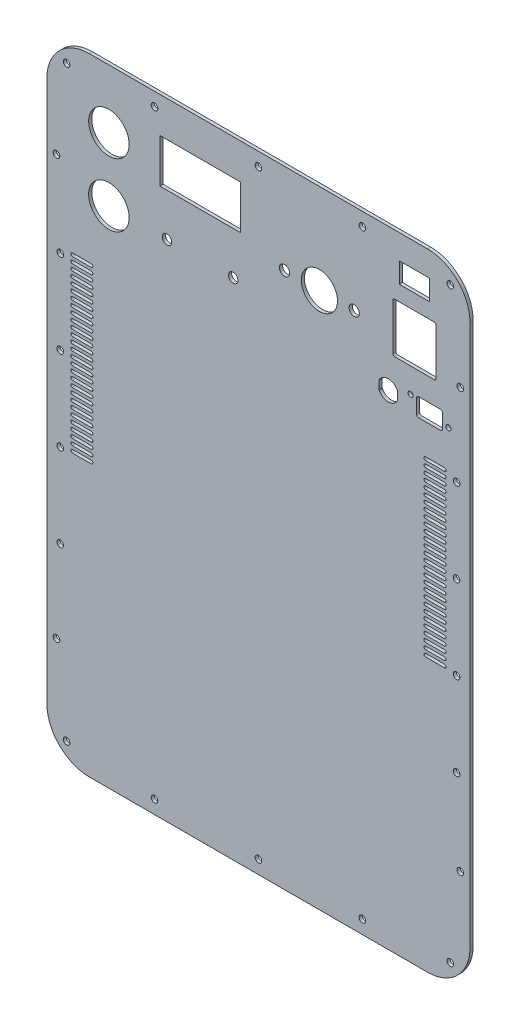
SolidWorks part; units mm, degrees
ref_plane "Alzado" through (0, 0, 0) normal (0, 0, 1) x (1, 0, 0)
ref_plane "Planta" through (0, 0, 0) normal (0, 1, 0) x (1, 0, 0)
ref_plane "Vista lateral" through (0, 0, 0) normal (1, 0, 0) x (0, 0, -1)
sketch "Croquis1" plane through (0, 0, 0) normal (0, 0, 1) x (1, 0, 0)
  line L1 (-107.295, -198.81) -> (107.295, -198.81)
  line L2 (-134.295, -171.81) -> (-134.295, 171.81)
  line L3 (-107.295, 198.81) -> (107.295, 198.81)
  line L4 (134.295, -171.81) -> (134.295, 171.81)
  line L5 (-134.295, -198.81) -> (134.295, 198.81) construction
  line L6 (-134.295, 198.81) -> (134.295, -198.81) construction
  arc A0 (-107.295, -198.81) -> (-134.295, -171.81) centre (-107.295, -171.81) cw
  arc A1 (107.295, -198.81) -> (134.295, -171.81) centre (107.295, -171.81) ccw
  arc A2 (107.295, 198.81) -> (134.295, 171.81) centre (107.295, 171.81) cw
  arc A3 (-134.295, 171.81) -> (-107.295, 198.81) centre (-107.295, 171.81) cw
  point P0 (0, 0)
  dimension "D3" = 27
  dimension "D1" = 268.59
  dimension "D2" = 397.62
extrude "Saliente-Extruir1" add sketch "Croquis1" along normal blind 2
sketch "Croquis2" plane through (0, 0, 2) normal (0, 0, 1) x (1, 0, 0)
  line L0 (107.295, 198.81) -> (-107.295, 198.81) construction
  line L1 (-134.295, 171.81) -> (-134.295, -171.81) construction
  line L2 (134.295, -171.81) -> (134.295, 171.81) construction
  line L4 (-62.615, 148.39) -> (-11.315, 148.39)
  line L5 (-62.615, 148.39) -> (-62.615, 176.19)
  line L6 (-62.615, 176.19) -> (-11.315, 176.19)
  line L7 (-11.315, 148.39) -> (-11.315, 176.19)
  line L8 (-62.615, 148.39) -> (-11.315, 176.19) construction
  line L9 (-62.615, 176.19) -> (-11.315, 148.39) construction
  line L10 (89.385, 170.39) -> (108.685, 170.39)
  line L11 (89.385, 170.39) -> (89.385, 183.29)
  line L12 (89.385, 183.29) -> (108.685, 183.29)
  line L13 (108.685, 170.39) -> (108.685, 183.29)
  line L14 (89.385, 170.39) -> (108.685, 183.29) construction
  line L15 (89.385, 183.29) -> (108.685, 170.39) construction
  line L16 (86.385, 129.09) -> (111.685, 129.09)
  line L17 (85.385, 130.09) -> (85.385, 159.69)
  line L18 (86.385, 160.69) -> (111.685, 160.69)
  line L19 (112.685, 130.09) -> (112.685, 159.69)
  line L20 (85.385, 129.09) -> (112.685, 160.69) construction
  line L21 (85.385, 160.69) -> (112.685, 129.09) construction
  line L22 (101.67, 103.165) -> (115.46, 103.165)
  line L23 (100.29, 104.545) -> (100.29, 113.335)
  line L24 (101.67, 114.715) -> (115.46, 114.715)
  line L25 (116.84, 104.545) -> (116.84, 113.335)
  line L26 (100.29, 103.165) -> (116.84, 114.715) construction
  line L27 (100.29, 114.715) -> (116.84, 103.165) construction
  line L29 (76.59, 105.9387) -> (76.59, 111.2413)
  line L31 (88.24, 105.9387) -> (88.24, 111.2413)
  line L32 (76.6043, 105.9076) -> (88.2257, 111.2724) construction
  line L33 (76.59, 111.279) -> (88.2257, 105.9076) construction
  circle A0 centre (-94.915, 161.54) radius 12.85
  circle A1 centre (-94.915, 121.27) radius 12.85
  circle A2 centre (-58.015, 121.27) radius 3
  circle A3 centre (-16.015, 121.27) radius 3
  circle A4 centre (38.695, 141.62) radius 11.5
  circle A5 centre (16.595, 141.62) radius 3.25
  circle A6 centre (60.795, 141.62) radius 3.25
  arc A7 (111.685, 129.09) -> (112.685, 130.09) centre (111.685, 130.09) ccw
  arc A8 (86.385, 129.09) -> (85.385, 130.09) centre (86.385, 130.09) cw
  arc A9 (85.385, 159.69) -> (86.385, 160.69) centre (86.385, 159.69) cw
  arc A10 (111.685, 160.69) -> (112.685, 159.69) centre (111.685, 159.69) cw
  circle A11 centre (120.565, 107.09) radius 1.625
  circle A12 centre (96.565, 113.44) radius 1.625
  arc A13 (100.29, 113.335) -> (101.67, 114.715) centre (101.67, 113.335) cw
  arc A14 (101.67, 103.165) -> (100.29, 104.545) centre (101.67, 104.545) cw
  arc A15 (115.46, 103.165) -> (116.84, 104.545) centre (115.46, 104.545) ccw
  arc A16 (115.46, 114.715) -> (116.84, 113.335) centre (115.46, 113.335) cw
  arc A17 (76.59, 105.9387) -> (88.24, 105.9387) centre (82.415, 108.59) ccw
  arc A18 (88.24, 111.2413) -> (76.59, 111.2413) centre (82.415, 108.59) ccw
  point P18 (99.035, 176.84)
  point P24 (-36.965, 162.29)
  point P30 (99.035, 144.89)
  point P47 (108.565, 108.94)
  dimension "D1" = 25.7
  dimension "D2" = 37.27
  dimension "D3" = 39.38
  dimension "D4" = 40.27
  dimension "D5" = 39.38
  dimension "D6" = 6
  dimension "D7" = 42
  dimension "D8" = 36.9
  dimension "D9" = 77.54
  dimension "D10" = 77.54
  dimension "D11" = 57.19
  dimension "D12" = 6.5
  dimension "D13" = 22.1
  dimension "D14" = 22.1
  dimension "D15" = 23
  dimension "D16" = 95.6
  dimension "D29" = 1
  dimension "D32" = 1.85
  dimension "D33" = 6.35
  dimension "D36" = 3.25
  dimension "D37" = 1.38
  dimension "D38" = 24
  dimension "D40" = 12.8
  dimension "D17" = 51.3
  dimension "D18" = 27.8
  dimension "D19" = 36.52
  dimension "D20" = 97.33
  dimension "D21" = 19.3
  dimension "D22" = 12.9
  dimension "D23" = 21.97
  dimension "D24" = 35.26
  dimension "D25" = 27.3
  dimension "D26" = 31.6
  dimension "D27" = 53.92
  dimension "D28" = 35.26
  dimension "D30" = 11.55
  dimension "D31" = 16.55
  dimension "D34" = 25.73
  dimension "D35" = 89.87
  dimension "D39" = 12
  dimension "D41" = 11.65
  dimension "D42" = 90.22
  dimension "D43" = 51.88
extrude "Cortar-Extruir1" cut sketch "Croquis2" against normal through all
sketch "Croquis3" plane through (0, 0, 2) normal (0, 0, 1) x (1, 0, 0)
  line L0 (0, 217.0296) -> (0, -209.3) construction
  line L1 (148.9664, 0) -> (-157.6291, 0) construction
  line L2 (107.295, 198.81) -> (-107.295, 198.81) construction
  line L3 (-134.295, 171.81) -> (-134.295, -171.81) construction
  circle A0 centre (0, 190.26) radius 2.095
  circle A1 centre (-65.96, 190.26) radius 2.095
  circle A2 centre (-121.78, 186.3) radius 2.095
  circle A3 centre (65.96, 190.26) radius 2.095
  circle A4 centre (121.78, 186.3) radius 2.095
  circle A5 centre (121.78, -186.3) radius 2.095
  circle A6 centre (65.96, -190.26) radius 2.095
  circle A7 centre (0, -190.26) radius 2.095
  circle A8 centre (-65.96, -190.26) radius 2.095
  circle A9 centre (-121.78, -186.3) radius 2.095
  circle A10 centre (-125.745, 26.61) radius 2.095
  circle A11 centre (-125.745, 79.83) radius 2.095
  circle A12 centre (-128.165, 133.05) radius 2.095
  circle A13 centre (-125.745, -26.61) radius 2.095
  circle A14 centre (-125.745, -79.83) radius 2.095
  circle A15 centre (-128.165, -133.05) radius 2.095
  circle A16 centre (128.165, -133.05) radius 2.095
  circle A17 centre (125.745, -79.83) radius 2.095
  circle A18 centre (125.745, -26.61) radius 2.095
  circle A19 centre (125.745, 26.61) radius 2.095
  circle A20 centre (125.745, 79.83) radius 2.095
  circle A21 centre (128.165, 133.05) radius 2.095
  dimension "D1" = 4.19
  dimension "D2" = 8.55
  dimension "D3" = 65.96
  dimension "D4" = 55.82
  dimension "D5" = 12.51
  dimension "D7" = 4.19
  dimension "D8" = 8.55
  dimension "D9" = 26.61
  dimension "D10" = 53.22
  dimension "D11" = 8.55
  dimension "D12" = 53.22
  dimension "D13" = 6.13
  dimension "D6" = 8.55
extrude "Cortar-Extruir2" cut sketch "Croquis3" against normal through all
sketch "Croquis4" plane through (0, 0, 2) normal (0, 0, 1) x (1, 0, 0)
  line L0 (0, 198.81) -> (0, -99.1567) construction
  line L1 (107.295, 198.81) -> (-107.295, 198.81) construction
  line L2 (-118.065, 82.89) -> (-106.065, 82.89) construction
  line L3 (-118.065, 83.89) -> (-106.065, 83.89)
  line L4 (-118.065, 81.89) -> (-106.065, 81.89)
  line L6 (-134.295, 171.81) -> (-134.295, -171.81) construction
  line L7 (-118.065, 78.89) -> (-106.065, 78.89) construction
  line L8 (-118.065, 79.89) -> (-106.065, 79.89)
  line L9 (-118.065, 77.89) -> (-106.065, 77.89)
  line L10 (-118.065, 74.89) -> (-106.065, 74.89) construction
  line L11 (-118.065, 75.89) -> (-106.065, 75.89)
  line L12 (-118.065, 73.89) -> (-106.065, 73.89)
  line L13 (-118.065, 70.89) -> (-106.065, 70.89) construction
  line L14 (-118.065, 71.89) -> (-106.065, 71.89)
  line L15 (-118.065, 69.89) -> (-106.065, 69.89)
  line L16 (-118.065, 66.89) -> (-106.065, 66.89) construction
  line L17 (-118.065, 67.89) -> (-106.065, 67.89)
  line L18 (-118.065, 65.89) -> (-106.065, 65.89)
  line L19 (-118.065, 62.89) -> (-106.065, 62.89) construction
  line L20 (-118.065, 63.89) -> (-106.065, 63.89)
  line L21 (-118.065, 61.89) -> (-106.065, 61.89)
  line L22 (-118.065, 58.89) -> (-106.065, 58.89) construction
  line L23 (-118.065, 59.89) -> (-106.065, 59.89)
  line L24 (-118.065, 57.89) -> (-106.065, 57.89)
  line L25 (-118.065, 54.89) -> (-106.065, 54.89) construction
  line L26 (-118.065, 55.89) -> (-106.065, 55.89)
  line L27 (-118.065, 53.89) -> (-106.065, 53.89)
  line L28 (-118.065, 50.89) -> (-106.065, 50.89) construction
  line L29 (-118.065, 51.89) -> (-106.065, 51.89)
  line L30 (-118.065, 49.89) -> (-106.065, 49.89)
  line L31 (-118.065, 46.89) -> (-106.065, 46.89) construction
  line L32 (-118.065, 47.89) -> (-106.065, 47.89)
  line L33 (-118.065, 45.89) -> (-106.065, 45.89)
  line L34 (-118.065, 42.89) -> (-106.065, 42.89) construction
  line L35 (-118.065, 43.89) -> (-106.065, 43.89)
  line L36 (-118.065, 41.89) -> (-106.065, 41.89)
  line L37 (-118.065, 38.89) -> (-106.065, 38.89) construction
  line L38 (-118.065, 39.89) -> (-106.065, 39.89)
  line L39 (-118.065, 37.89) -> (-106.065, 37.89)
  line L40 (-118.065, 34.89) -> (-106.065, 34.89) construction
  line L41 (-118.065, 35.89) -> (-106.065, 35.89)
  line L42 (-118.065, 33.89) -> (-106.065, 33.89)
  line L43 (-118.065, 30.89) -> (-106.065, 30.89) construction
  line L44 (-118.065, 31.89) -> (-106.065, 31.89)
  line L45 (-118.065, 29.89) -> (-106.065, 29.89)
  line L46 (-118.065, 26.89) -> (-106.065, 26.89) construction
  line L47 (-118.065, 27.89) -> (-106.065, 27.89)
  line L48 (-118.065, 25.89) -> (-106.065, 25.89)
  line L49 (-118.065, 22.89) -> (-106.065, 22.89) construction
  line L50 (-118.065, 23.89) -> (-106.065, 23.89)
  line L51 (-118.065, 21.89) -> (-106.065, 21.89)
  line L52 (-118.065, 18.89) -> (-106.065, 18.89) construction
  line L53 (-118.065, 19.89) -> (-106.065, 19.89)
  line L54 (-118.065, 17.89) -> (-106.065, 17.89)
  line L55 (-118.065, 14.89) -> (-106.065, 14.89) construction
  line L56 (-118.065, 15.89) -> (-106.065, 15.89)
  line L57 (-118.065, 13.89) -> (-106.065, 13.89)
  line L58 (-118.065, 10.89) -> (-106.065, 10.89) construction
  line L59 (-118.065, 11.89) -> (-106.065, 11.89)
  line L60 (-118.065, 9.89) -> (-106.065, 9.89)
  line L61 (-118.065, 6.89) -> (-106.065, 6.89) construction
  line L62 (-118.065, 7.89) -> (-106.065, 7.89)
  line L63 (-118.065, 5.89) -> (-106.065, 5.89)
  line L64 (-118.065, 2.89) -> (-106.065, 2.89) construction
  line L65 (-118.065, 3.89) -> (-106.065, 3.89)
  line L66 (-118.065, 1.89) -> (-106.065, 1.89)
  line L67 (-118.065, -1.11) -> (-106.065, -1.11) construction
  line L68 (-118.065, -0.11) -> (-106.065, -0.11)
  line L69 (-118.065, -2.11) -> (-106.065, -2.11)
  line L70 (-118.065, -5.11) -> (-106.065, -5.11) construction
  line L71 (-118.065, -4.11) -> (-106.065, -4.11)
  line L72 (-118.065, -6.11) -> (-106.065, -6.11)
  line L73 (-118.065, -9.11) -> (-106.065, -9.11) construction
  line L74 (-118.065, -8.11) -> (-106.065, -8.11)
  line L75 (-118.065, -10.11) -> (-106.065, -10.11)
  line L76 (-118.065, -13.11) -> (-106.065, -13.11) construction
  line L77 (-118.065, -12.11) -> (-106.065, -12.11)
  line L78 (-118.065, -14.11) -> (-106.065, -14.11)
  line L79 (-118.065, -17.11) -> (-106.065, -17.11) construction
  line L80 (-118.065, -16.11) -> (-106.065, -16.11)
  line L81 (-118.065, -18.11) -> (-106.065, -18.11)
  line L82 (-118.065, -21.11) -> (-106.065, -21.11) construction
  line L83 (-118.065, -20.11) -> (-106.065, -20.11)
  line L84 (-118.065, -22.11) -> (-106.065, -22.11)
  line L85 (-118.065, -25.11) -> (-106.065, -25.11) construction
  line L86 (-118.065, -24.11) -> (-106.065, -24.11)
  line L87 (-118.065, -26.11) -> (-106.065, -26.11)
  line L88 (-150.525, 82.89) -> (-162.525, 82.89) construction
  line L89 (-150.525, 83.89) -> (-162.525, 83.89)
  line L90 (-150.525, 81.89) -> (-162.525, 81.89)
  line L91 (118.065, -25.11) -> (106.065, -25.11) construction
  line L92 (118.065, -24.11) -> (106.065, -24.11)
  line L93 (118.065, -26.11) -> (106.065, -26.11)
  line L94 (118.065, -21.11) -> (106.065, -21.11) construction
  line L95 (118.065, -20.11) -> (106.065, -20.11)
  line L96 (118.065, -22.11) -> (106.065, -22.11)
  line L97 (118.065, -17.11) -> (106.065, -17.11) construction
  line L98 (118.065, -16.11) -> (106.065, -16.11)
  line L99 (118.065, -18.11) -> (106.065, -18.11)
  line L100 (118.065, -13.11) -> (106.065, -13.11) construction
  line L101 (118.065, -12.11) -> (106.065, -12.11)
  line L102 (118.065, -14.11) -> (106.065, -14.11)
  line L103 (118.065, -9.11) -> (106.065, -9.11) construction
  line L104 (118.065, -8.11) -> (106.065, -8.11)
  line L105 (118.065, -10.11) -> (106.065, -10.11)
  line L106 (118.065, -5.11) -> (106.065, -5.11) construction
  line L107 (118.065, -4.11) -> (106.065, -4.11)
  line L108 (118.065, -6.11) -> (106.065, -6.11)
  line L109 (118.065, -1.11) -> (106.065, -1.11) construction
  line L110 (118.065, -0.11) -> (106.065, -0.11)
  line L111 (118.065, -2.11) -> (106.065, -2.11)
  line L112 (118.065, 2.89) -> (106.065, 2.89) construction
  line L113 (118.065, 3.89) -> (106.065, 3.89)
  line L114 (118.065, 1.89) -> (106.065, 1.89)
  line L115 (118.065, 6.89) -> (106.065, 6.89) construction
  line L116 (118.065, 7.89) -> (106.065, 7.89)
  line L117 (118.065, 5.89) -> (106.065, 5.89)
  line L118 (118.065, 10.89) -> (106.065, 10.89) construction
  line L119 (118.065, 11.89) -> (106.065, 11.89)
  line L120 (118.065, 9.89) -> (106.065, 9.89)
  line L121 (118.065, 14.89) -> (106.065, 14.89) construction
  line L122 (118.065, 15.89) -> (106.065, 15.89)
  line L123 (118.065, 13.89) -> (106.065, 13.89)
  line L124 (118.065, 18.89) -> (106.065, 18.89) construction
  line L125 (118.065, 19.89) -> (106.065, 19.89)
  line L126 (118.065, 17.89) -> (106.065, 17.89)
  line L127 (118.065, 22.89) -> (106.065, 22.89) construction
  line L128 (118.065, 23.89) -> (106.065, 23.89)
  line L129 (118.065, 21.89) -> (106.065, 21.89)
  line L130 (118.065, 26.89) -> (106.065, 26.89) construction
  line L131 (118.065, 27.89) -> (106.065, 27.89)
  line L132 (118.065, 25.89) -> (106.065, 25.89)
  line L133 (118.065, 30.89) -> (106.065, 30.89) construction
  line L134 (118.065, 31.89) -> (106.065, 31.89)
  line L135 (118.065, 29.89) -> (106.065, 29.89)
  line L136 (118.065, 34.89) -> (106.065, 34.89) construction
  line L137 (118.065, 35.89) -> (106.065, 35.89)
  line L138 (118.065, 33.89) -> (106.065, 33.89)
  line L139 (118.065, 38.89) -> (106.065, 38.89) construction
  line L140 (118.065, 39.89) -> (106.065, 39.89)
  line L141 (118.065, 37.89) -> (106.065, 37.89)
  line L142 (118.065, 42.89) -> (106.065, 42.89) construction
  line L143 (118.065, 43.89) -> (106.065, 43.89)
  line L144 (118.065, 41.89) -> (106.065, 41.89)
  line L145 (118.065, 46.89) -> (106.065, 46.89) construction
  line L146 (118.065, 47.89) -> (106.065, 47.89)
  line L147 (118.065, 45.89) -> (106.065, 45.89)
  line L148 (118.065, 50.89) -> (106.065, 50.89) construction
  line L149 (118.065, 51.89) -> (106.065, 51.89)
  line L150 (118.065, 49.89) -> (106.065, 49.89)
  line L151 (118.065, 54.89) -> (106.065, 54.89) construction
  line L152 (118.065, 55.89) -> (106.065, 55.89)
  line L153 (118.065, 53.89) -> (106.065, 53.89)
  line L154 (118.065, 58.89) -> (106.065, 58.89) construction
  line L155 (118.065, 59.89) -> (106.065, 59.89)
  line L156 (118.065, 57.89) -> (106.065, 57.89)
  line L157 (118.065, 62.89) -> (106.065, 62.89) construction
  line L158 (118.065, 63.89) -> (106.065, 63.89)
  line L159 (118.065, 61.89) -> (106.065, 61.89)
  line L160 (118.065, 66.89) -> (106.065, 66.89) construction
  line L161 (118.065, 67.89) -> (106.065, 67.89)
  line L162 (118.065, 65.89) -> (106.065, 65.89)
  line L163 (118.065, 70.89) -> (106.065, 70.89) construction
  line L164 (118.065, 71.89) -> (106.065, 71.89)
  line L165 (118.065, 69.89) -> (106.065, 69.89)
  line L166 (118.065, 74.89) -> (106.065, 74.89) construction
  line L167 (118.065, 75.89) -> (106.065, 75.89)
  line L168 (118.065, 73.89) -> (106.065, 73.89)
  line L169 (118.065, 78.89) -> (106.065, 78.89) construction
  line L170 (118.065, 79.89) -> (106.065, 79.89)
  line L171 (118.065, 77.89) -> (106.065, 77.89)
  line L172 (118.065, 82.89) -> (106.065, 82.89) construction
  line L173 (118.065, 83.89) -> (106.065, 83.89)
  line L174 (118.065, 81.89) -> (106.065, 81.89)
  arc A0 (-118.065, 83.89) -> (-118.065, 81.89) centre (-118.065, 82.89) ccw
  arc A1 (-106.065, 81.89) -> (-106.065, 83.89) centre (-106.065, 82.89) ccw
  arc A2 (-118.065, 79.89) -> (-118.065, 77.89) centre (-118.065, 78.89) ccw
  arc A3 (-106.065, 77.89) -> (-106.065, 79.89) centre (-106.065, 78.89) ccw
  arc A4 (-118.065, 75.89) -> (-118.065, 73.89) centre (-118.065, 74.89) ccw
  arc A5 (-106.065, 73.89) -> (-106.065, 75.89) centre (-106.065, 74.89) ccw
  arc A6 (-118.065, 71.89) -> (-118.065, 69.89) centre (-118.065, 70.89) ccw
  arc A7 (-106.065, 69.89) -> (-106.065, 71.89) centre (-106.065, 70.89) ccw
  arc A8 (-118.065, 67.89) -> (-118.065, 65.89) centre (-118.065, 66.89) ccw
  arc A9 (-106.065, 65.89) -> (-106.065, 67.89) centre (-106.065, 66.89) ccw
  arc A10 (-118.065, 63.89) -> (-118.065, 61.89) centre (-118.065, 62.89) ccw
  arc A11 (-106.065, 61.89) -> (-106.065, 63.89) centre (-106.065, 62.89) ccw
  arc A12 (-118.065, 59.89) -> (-118.065, 57.89) centre (-118.065, 58.89) ccw
  arc A13 (-106.065, 57.89) -> (-106.065, 59.89) centre (-106.065, 58.89) ccw
  arc A14 (-118.065, 55.89) -> (-118.065, 53.89) centre (-118.065, 54.89) ccw
  arc A15 (-106.065, 53.89) -> (-106.065, 55.89) centre (-106.065, 54.89) ccw
  arc A16 (-118.065, 51.89) -> (-118.065, 49.89) centre (-118.065, 50.89) ccw
  arc A17 (-106.065, 49.89) -> (-106.065, 51.89) centre (-106.065, 50.89) ccw
  arc A18 (-118.065, 47.89) -> (-118.065, 45.89) centre (-118.065, 46.89) ccw
  arc A19 (-106.065, 45.89) -> (-106.065, 47.89) centre (-106.065, 46.89) ccw
  arc A20 (-118.065, 43.89) -> (-118.065, 41.89) centre (-118.065, 42.89) ccw
  arc A21 (-106.065, 41.89) -> (-106.065, 43.89) centre (-106.065, 42.89) ccw
  arc A22 (-118.065, 39.89) -> (-118.065, 37.89) centre (-118.065, 38.89) ccw
  arc A23 (-106.065, 37.89) -> (-106.065, 39.89) centre (-106.065, 38.89) ccw
  arc A24 (-118.065, 35.89) -> (-118.065, 33.89) centre (-118.065, 34.89) ccw
  arc A25 (-106.065, 33.89) -> (-106.065, 35.89) centre (-106.065, 34.89) ccw
  arc A26 (-118.065, 31.89) -> (-118.065, 29.89) centre (-118.065, 30.89) ccw
  arc A27 (-106.065, 29.89) -> (-106.065, 31.89) centre (-106.065, 30.89) ccw
  arc A28 (-118.065, 27.89) -> (-118.065, 25.89) centre (-118.065, 26.89) ccw
  arc A29 (-106.065, 25.89) -> (-106.065, 27.89) centre (-106.065, 26.89) ccw
  arc A30 (-118.065, 23.89) -> (-118.065, 21.89) centre (-118.065, 22.89) ccw
  arc A31 (-106.065, 21.89) -> (-106.065, 23.89) centre (-106.065, 22.89) ccw
  arc A32 (-118.065, 19.89) -> (-118.065, 17.89) centre (-118.065, 18.89) ccw
  arc A33 (-106.065, 17.89) -> (-106.065, 19.89) centre (-106.065, 18.89) ccw
  arc A34 (-118.065, 15.89) -> (-118.065, 13.89) centre (-118.065, 14.89) ccw
  arc A35 (-106.065, 13.89) -> (-106.065, 15.89) centre (-106.065, 14.89) ccw
  arc A36 (-118.065, 11.89) -> (-118.065, 9.89) centre (-118.065, 10.89) ccw
  arc A37 (-106.065, 9.89) -> (-106.065, 11.89) centre (-106.065, 10.89) ccw
  arc A38 (-118.065, 7.89) -> (-118.065, 5.89) centre (-118.065, 6.89) ccw
  arc A39 (-106.065, 5.89) -> (-106.065, 7.89) centre (-106.065, 6.89) ccw
  arc A40 (-118.065, 3.89) -> (-118.065, 1.89) centre (-118.065, 2.89) ccw
  arc A41 (-106.065, 1.89) -> (-106.065, 3.89) centre (-106.065, 2.89) ccw
  arc A42 (-118.065, -0.11) -> (-118.065, -2.11) centre (-118.065, -1.11) ccw
  arc A43 (-106.065, -2.11) -> (-106.065, -0.11) centre (-106.065, -1.11) ccw
  arc A44 (-118.065, -4.11) -> (-118.065, -6.11) centre (-118.065, -5.11) ccw
  arc A45 (-106.065, -6.11) -> (-106.065, -4.11) centre (-106.065, -5.11) ccw
  arc A46 (-118.065, -8.11) -> (-118.065, -10.11) centre (-118.065, -9.11) ccw
  arc A47 (-106.065, -10.11) -> (-106.065, -8.11) centre (-106.065, -9.11) ccw
  arc A48 (-118.065, -12.11) -> (-118.065, -14.11) centre (-118.065, -13.11) ccw
  arc A49 (-106.065, -14.11) -> (-106.065, -12.11) centre (-106.065, -13.11) ccw
  arc A50 (-118.065, -16.11) -> (-118.065, -18.11) centre (-118.065, -17.11) ccw
  arc A51 (-106.065, -18.11) -> (-106.065, -16.11) centre (-106.065, -17.11) ccw
  arc A52 (-118.065, -20.11) -> (-118.065, -22.11) centre (-118.065, -21.11) ccw
  arc A53 (-106.065, -22.11) -> (-106.065, -20.11) centre (-106.065, -21.11) ccw
  arc A54 (-118.065, -24.11) -> (-118.065, -26.11) centre (-118.065, -25.11) ccw
  arc A55 (-106.065, -26.11) -> (-106.065, -24.11) centre (-106.065, -25.11) ccw
  arc A56 (-150.525, 83.89) -> (-150.525, 81.89) centre (-150.525, 82.89) cw
  arc A57 (-162.525, 81.89) -> (-162.525, 83.89) centre (-162.525, 82.89) cw
  arc A58 (118.065, -24.11) -> (118.065, -26.11) centre (118.065, -25.11) cw
  arc A59 (106.065, -26.11) -> (106.065, -24.11) centre (106.065, -25.11) cw
  arc A60 (118.065, -20.11) -> (118.065, -22.11) centre (118.065, -21.11) cw
  arc A61 (106.065, -22.11) -> (106.065, -20.11) centre (106.065, -21.11) cw
  arc A62 (118.065, -16.11) -> (118.065, -18.11) centre (118.065, -17.11) cw
  arc A63 (106.065, -18.11) -> (106.065, -16.11) centre (106.065, -17.11) cw
  arc A64 (118.065, -12.11) -> (118.065, -14.11) centre (118.065, -13.11) cw
  arc A65 (106.065, -14.11) -> (106.065, -12.11) centre (106.065, -13.11) cw
  arc A66 (118.065, -8.11) -> (118.065, -10.11) centre (118.065, -9.11) cw
  arc A67 (106.065, -10.11) -> (106.065, -8.11) centre (106.065, -9.11) cw
  arc A68 (118.065, -4.11) -> (118.065, -6.11) centre (118.065, -5.11) cw
  arc A69 (106.065, -6.11) -> (106.065, -4.11) centre (106.065, -5.11) cw
  arc A70 (118.065, -0.11) -> (118.065, -2.11) centre (118.065, -1.11) cw
  arc A71 (106.065, -2.11) -> (106.065, -0.11) centre (106.065, -1.11) cw
  arc A72 (118.065, 3.89) -> (118.065, 1.89) centre (118.065, 2.89) cw
  arc A73 (106.065, 1.89) -> (106.065, 3.89) centre (106.065, 2.89) cw
  arc A74 (118.065, 7.89) -> (118.065, 5.89) centre (118.065, 6.89) cw
  arc A75 (106.065, 5.89) -> (106.065, 7.89) centre (106.065, 6.89) cw
  arc A76 (118.065, 11.89) -> (118.065, 9.89) centre (118.065, 10.89) cw
  arc A77 (106.065, 9.89) -> (106.065, 11.89) centre (106.065, 10.89) cw
  arc A78 (118.065, 15.89) -> (118.065, 13.89) centre (118.065, 14.89) cw
  arc A79 (106.065, 13.89) -> (106.065, 15.89) centre (106.065, 14.89) cw
  arc A80 (118.065, 19.89) -> (118.065, 17.89) centre (118.065, 18.89) cw
  arc A81 (106.065, 17.89) -> (106.065, 19.89) centre (106.065, 18.89) cw
  arc A82 (118.065, 23.89) -> (118.065, 21.89) centre (118.065, 22.89) cw
  arc A83 (106.065, 21.89) -> (106.065, 23.89) centre (106.065, 22.89) cw
  arc A84 (118.065, 27.89) -> (118.065, 25.89) centre (118.065, 26.89) cw
  arc A85 (106.065, 25.89) -> (106.065, 27.89) centre (106.065, 26.89) cw
  arc A86 (118.065, 31.89) -> (118.065, 29.89) centre (118.065, 30.89) cw
  arc A87 (106.065, 29.89) -> (106.065, 31.89) centre (106.065, 30.89) cw
  arc A88 (118.065, 35.89) -> (118.065, 33.89) centre (118.065, 34.89) cw
  arc A89 (106.065, 33.89) -> (106.065, 35.89) centre (106.065, 34.89) cw
  arc A90 (118.065, 39.89) -> (118.065, 37.89) centre (118.065, 38.89) cw
  arc A91 (106.065, 37.89) -> (106.065, 39.89) centre (106.065, 38.89) cw
  arc A92 (118.065, 43.89) -> (118.065, 41.89) centre (118.065, 42.89) cw
  arc A93 (106.065, 41.89) -> (106.065, 43.89) centre (106.065, 42.89) cw
  arc A94 (118.065, 47.89) -> (118.065, 45.89) centre (118.065, 46.89) cw
  arc A95 (106.065, 45.89) -> (106.065, 47.89) centre (106.065, 46.89) cw
  arc A96 (118.065, 51.89) -> (118.065, 49.89) centre (118.065, 50.89) cw
  arc A97 (106.065, 49.89) -> (106.065, 51.89) centre (106.065, 50.89) cw
  arc A98 (118.065, 55.89) -> (118.065, 53.89) centre (118.065, 54.89) cw
  arc A99 (106.065, 53.89) -> (106.065, 55.89) centre (106.065, 54.89) cw
  arc A100 (118.065, 59.89) -> (118.065, 57.89) centre (118.065, 58.89) cw
  arc A101 (106.065, 57.89) -> (106.065, 59.89) centre (106.065, 58.89) cw
  arc A102 (118.065, 63.89) -> (118.065, 61.89) centre (118.065, 62.89) cw
  arc A103 (106.065, 61.89) -> (106.065, 63.89) centre (106.065, 62.89) cw
  arc A104 (118.065, 67.89) -> (118.065, 65.89) centre (118.065, 66.89) cw
  arc A105 (106.065, 65.89) -> (106.065, 67.89) centre (106.065, 66.89) cw
  arc A106 (118.065, 71.89) -> (118.065, 69.89) centre (118.065, 70.89) cw
  arc A107 (106.065, 69.89) -> (106.065, 71.89) centre (106.065, 70.89) cw
  arc A108 (118.065, 75.89) -> (118.065, 73.89) centre (118.065, 74.89) cw
  arc A109 (106.065, 73.89) -> (106.065, 75.89) centre (106.065, 74.89) cw
  arc A110 (118.065, 79.89) -> (118.065, 77.89) centre (118.065, 78.89) cw
  arc A111 (106.065, 77.89) -> (106.065, 79.89) centre (106.065, 78.89) cw
  arc A112 (118.065, 83.89) -> (118.065, 81.89) centre (118.065, 82.89) cw
  arc A113 (106.065, 81.89) -> (106.065, 83.89) centre (106.065, 82.89) cw
  point P8 (-112.065, 82.89)
  point P19 (-112.065, 78.89)
  point P26 (-112.065, 74.89)
  point P33 (-112.065, 70.89)
  point P40 (-112.065, 66.89)
  point P47 (-112.065, 62.89)
  point P54 (-112.065, 58.89)
  point P61 (-112.065, 54.89)
  point P68 (-112.065, 50.89)
  point P75 (-112.065, 46.89)
  point P82 (-112.065, 42.89)
  point P89 (-112.065, 38.89)
  point P96 (-112.065, 34.89)
  point P103 (-112.065, 30.89)
  point P110 (-112.065, 26.89)
  point P117 (-112.065, 22.89)
  point P124 (-112.065, 18.89)
  point P131 (-112.065, 14.89)
  point P138 (-112.065, 10.89)
  point P145 (-112.065, 6.89)
  point P152 (-112.065, 2.89)
  point P159 (-112.065, -1.11)
  point P166 (-112.065, -5.11)
  point P173 (-112.065, -9.11)
  point P180 (-112.065, -13.11)
  point P187 (-112.065, -17.11)
  point P194 (-112.065, -21.11)
  point P201 (-112.065, -25.11)
  point P206 (-156.525, 82.89)
  point P213 (112.065, -25.11)
  point P220 (112.065, -21.11)
  point P227 (112.065, -17.11)
  point P234 (112.065, -13.11)
  point P241 (112.065, -9.11)
  point P248 (112.065, -5.11)
  point P255 (112.065, -1.11)
  point P262 (112.065, 2.89)
  point P269 (112.065, 6.89)
  point P276 (112.065, 10.89)
  point P283 (112.065, 14.89)
  point P290 (112.065, 18.89)
  point P297 (112.065, 22.89)
  point P304 (112.065, 26.89)
  point P311 (112.065, 30.89)
  point P318 (112.065, 34.89)
  point P325 (112.065, 38.89)
  point P332 (112.065, 42.89)
  point P339 (112.065, 46.89)
  point P346 (112.065, 50.89)
  point P353 (112.065, 54.89)
  point P360 (112.065, 58.89)
  point P367 (112.065, 62.89)
  point P374 (112.065, 66.89)
  point P381 (112.065, 70.89)
  point P388 (112.065, 74.89)
  point P395 (112.065, 78.89)
  point P402 (112.065, 82.89)
  dimension "D1" = 12
  dimension "D2" = 2
  dimension "D3" = 114.92
  dimension "D4" = 16.23
  dimension "D5" = 28
extrude "Cortar-Extruir3" cut sketch "Croquis4" against normal through all
